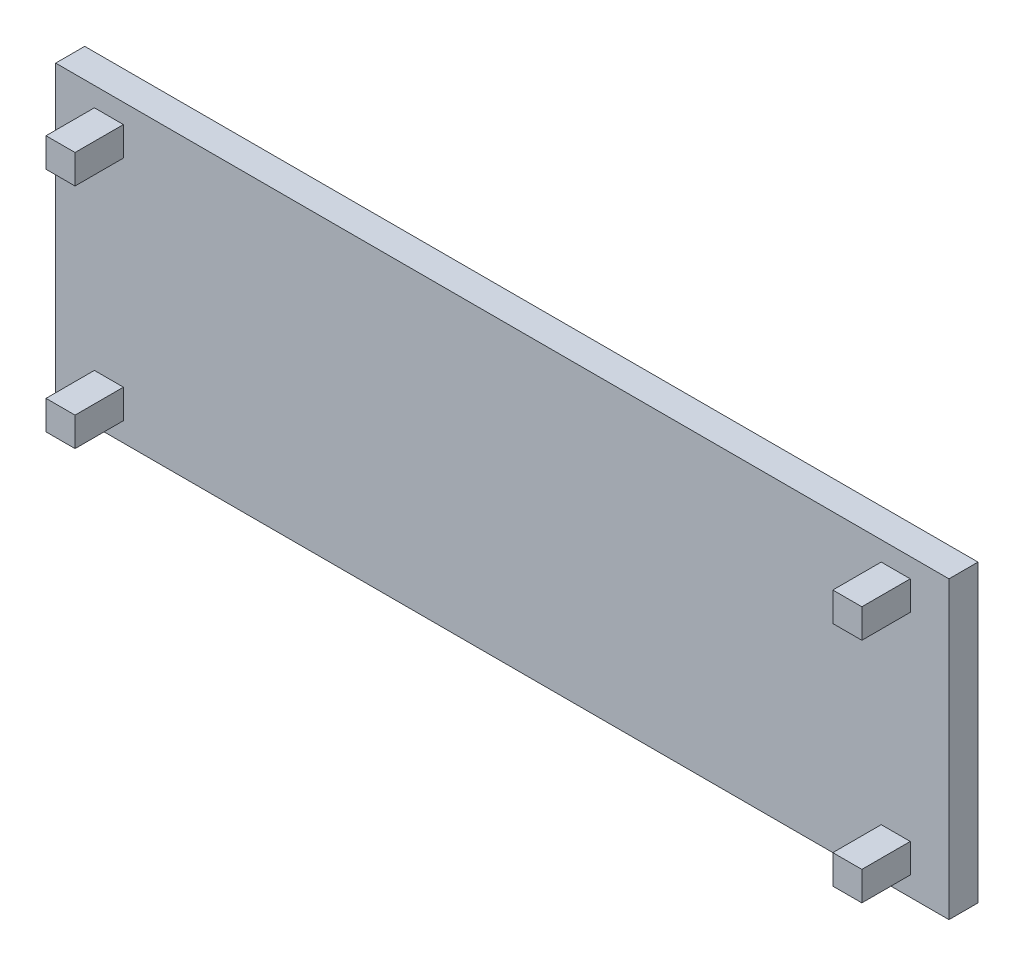
SolidWorks part; units mm, degrees
ref_plane "Front Plane" through (0, 0, 0) normal (0, 0, 1) x (1, 0, 0)
ref_plane "Top Plane" through (0, 0, 0) normal (0, 1, 0) x (1, 0, 0)
ref_plane "Right Plane" through (0, 0, 0) normal (1, 0, 0) x (0, 0, -1)
sketch "Sketch1" plane through (0, 0, 0) normal (0, 0, 1) x (1, 0, 0)
  line L8 (46.15, -14.65) -> (46.15, 15.85)
  line L9 (46.15, 15.85) -> (-46.15, 15.85)
  line L10 (-46.15, 15.85) -> (-46.15, -14.65)
  line L11 (-46.15, -14.65) -> (46.15, -14.65)
  line L12 (42.15, -12.65) -> (-42.15, -12.65)
  line L13 (42.15, 13.85) -> (42.15, -12.65)
  line L14 (-42.15, 13.85) -> (42.15, 13.85)
  line L15 (-42.15, 13.85) -> (-42.15, -12.65)
extrude "Boss-Extrude1" add sketch "Sketch1" along normal blind 3 contours L10 L11 L8 L9 L15 L14 L13 L12 | L14 L15 L12 L13
sketch "Sketch2" plane through (0, 0, 3) normal (0, 0, 1) x (1, 0, 0)
  line L0 (0, 0) -> (0, 30.6096) construction
  line L1 (-42.15, 13.85) -> (-39.15, 13.85)
  line L2 (-42.15, 13.85) -> (-42.15, 10.85)
  line L3 (-42.15, 10.85) -> (-39.15, 10.85)
  line L4 (-42.15, -12.65) -> (42.15, -12.65)
  line L5 (-42.15, 13.85) -> (-42.15, -12.65)
  line L6 (42.15, 13.85) -> (-42.15, 13.85)
  line L7 (42.15, -12.65) -> (42.15, 13.85)
  line L8 (-42.15, -12.65) -> (42.15, -12.65) construction
  line L9 (-42.15, 13.85) -> (-42.15, -12.65) construction
  line L10 (42.15, 13.85) -> (-42.15, 13.85) construction
  line L11 (42.15, -12.65) -> (42.15, 13.85) construction
  line L12 (-39.15, 13.85) -> (-39.15, 10.85)
  line L13 (0, 0) -> (10.9733, 0) construction
  line L14 (42.15, 10.85) -> (39.15, 10.85)
  line L15 (39.15, 13.85) -> (39.15, 10.85)
  line L20 (42.15, 13.85) -> (39.15, 13.85)
  line L21 (42.15, 13.85) -> (42.15, 10.85)
  line L23 (42.15, -12.65) -> (39.15, -12.65)
  line L24 (42.15, -12.65) -> (42.15, -9.65)
  line L25 (42.15, -9.65) -> (39.15, -9.65)
  line L26 (39.15, -12.65) -> (39.15, -9.65)
  line L27 (-42.15, -12.65) -> (-39.15, -12.65)
  line L28 (-42.15, -12.65) -> (-42.15, -9.65)
  line L29 (-42.15, -9.65) -> (-39.15, -9.65)
  line L30 (-39.15, -12.65) -> (-39.15, -9.65)
  dimension "D2" = 3
  dimension "D3" = 3
  dimension "D4" = 3
  dimension "D5" = 3
  dimension "D1" = 0
extrude "Boss-Extrude2" add sketch "Sketch2" along normal blind 5
